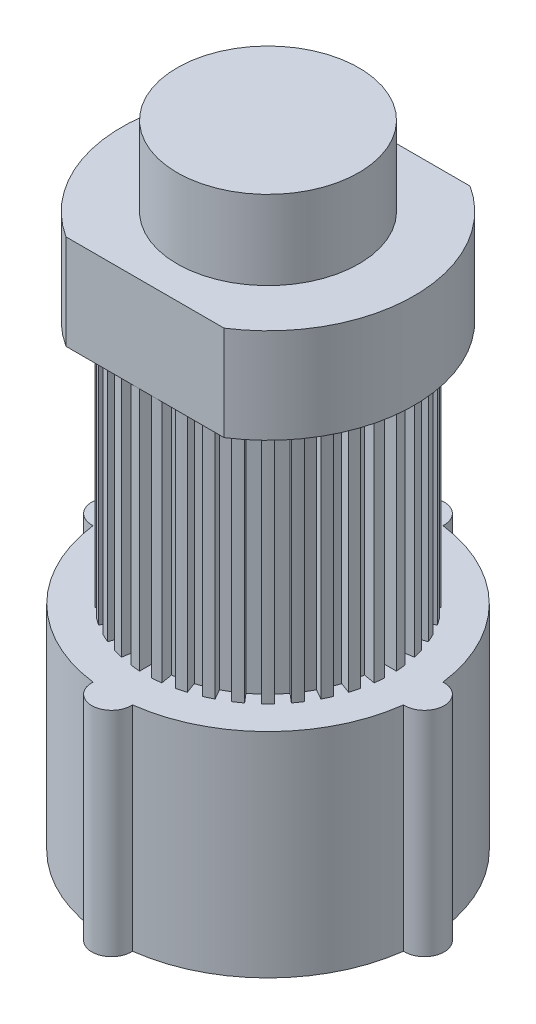
SolidWorks part; units mm, degrees
ref_plane "前视基准面" through (0, 0, 0) normal (0, 0, 1) x (1, 0, 0)
ref_plane "上视基准面" through (0, 0, 0) normal (0, 1, 0) x (1, 0, 0)
ref_plane "右视基准面" through (0, 0, 0) normal (1, 0, 0) x (0, 0, -1)
sketch "草图1" plane through (0, 0, 0) normal (0, 1, 0) x (1, 0, 0)
  circle A0 centre (0, 0) radius 8.2
  dimension "D1" = 16.4
extrude "凸台-拉伸1" add sketch "草图1" along normal blind 1
sketch "草图2" plane through (0, 1, 0) normal (0, 1, 0) x (1, 0, 0)
  line L0 (0, 12.8701) -> (0, -12.5799) construction
  line L1 (0, 0) -> (17.876, 0) construction
  circle A0 centre (0, 0) radius 19.799
  circle A2 centre (0, 19.799) radius 2.5
  circle A3 centre (19.799, 0) radius 2.5
  circle A4 centre (0, -19.799) radius 2.5
  circle A5 centre (-19.799, 0) radius 2.5
  point P19 (0, 0)
  circle M4 centre (0, 0) radius 8.2
  dimension "D2" = 5
  dimension "D3" = 4
  dimension "D4" = 28
extrude "凸台-拉伸2" add sketch "草图2" along normal blind 27 contours A5 A0 A4 A3 A2 M4 | M4 | A0 A3 | A0 A3 | A0 A2 | A0 A2 | A0 A5 | A0 A5 | A0 A4 | A0 A4
sketch "草图3" plane through (0, 28, 0) normal (0, 1, 0) x (1, 0, 0)
  circle A0 centre (0, 0) radius 15.5
  dimension "D1" = 31
extrude "凸台-拉伸4" add sketch "草图3" along normal offset from surface (43 mm away) 70 up to face at (0, 1, 8.2)
sketch "草图4" plane through (0, 71, 0) normal (0, 1, 0) x (1, 0, 0)
  circle A0 centre (0, 0) radius 11.5
  dimension "D1" = 23
extrude "凸台-拉伸5" add sketch "草图4" along normal blind 10
sketch "草图5" plane through (0, 71, 0) normal (0, 1, 0) x (1, 0, 0)
  line L0 (-18.5, 0) -> (18.5, 0) construction
  line L5 (-10, 15.5644) -> (10, 15.5644)
  line L6 (-10, -15.5644) -> (10, -15.5644)
  arc A8 (10, -15.5644) -> (10, 15.5644) centre (0, 0) ccw
  arc A9 (-10, -15.5644) -> (10, -15.5644) centre (0, 0) ccw construction
  arc A10 (10, 15.5644) -> (-10, 15.5644) centre (0, 0) ccw construction
  arc A11 (-10, 15.5644) -> (-10, -15.5644) centre (0, 0) ccw
  dimension "D2" = 20
  dimension "D1" = 37
extrude "凸台-拉伸6" add sketch "草图5" against normal blind 12
sketch "草图6" plane through (0, 28, 0) normal (0, 1, 0) x (1, 0, 0)
  line L0 (0, 0) -> (-18.4515, 0) construction
  line L2 (-17, -0.75) -> (-14, -0.75)
  line L3 (-17, -0.75) -> (-17, 0.75)
  line L4 (-17, 0.75) -> (-14, 0.75)
  line L5 (-14, -0.75) -> (-14, 0.75)
  line L6 (-17, -0.75) -> (-14, 0.75) construction
  line L7 (-17, 0.75) -> (-14, -0.75) construction
  circle A0 centre (0, 0) radius 15.5 construction
  circle A1 centre (0, 0) radius 15.5
  point P3 (-15.5, 0)
  circle M4 centre (0, 0) radius 15.5
  dimension "D1" = 1.5
  dimension "D2" = 3
extrude "切除-拉伸1" cut sketch "草图6" along normal up to surface (31 mm away) contours L4 L3 L2 M4 | L2 L5 L4 M4
pattern_circular "阵列(圆周)1" count 36 every 10 about axis through (0, 0, 0) along (0, 1, 0) of "切除-拉伸1"
sketch "草图7" plane through (0, 0, 0) normal (0, -1, 0) x (1, 0, 0)
  circle A1 centre (0, 0) radius 2.5
  dimension "D1" = 5
extrude "凸台-拉伸7" add sketch "草图7" along normal blind 10
ref_plane "基准面1" through (0, -9, 0) normal (0, -1, 0) x (-1, 0, 0)
sketch "草图9" plane through (0, -9, 0) normal (0, -1, 0) x (-1, 0, 0)
  line L1 (2.5, 0) -> (0, -2.5)
  line L2 (0, -2.5) -> (-2.5, 0)
  circle A1 centre (0, 0) radius 2.5
  arc A2 (-2.5, 0) -> (2.5, 0) centre (0, 0) ccw
  dimension "D1" = 0
extrude "切除-拉伸2" cut sketch "草图9" against normal blind 5 contours L2 A2 | L1 A2
sketch "草图10" plane through (0, 1, 0) normal (0, -1, 0) x (1, 0, 0)
  line L0 (-19.799, 0) -> (0, -19.799) construction
  line L1 (0, 0) -> (-9.8995, -9.8995) construction
  circle A0 centre (0, 0) radius 14.3677 construction
  arc A1 (-2.495, -19.6412) -> (2.495, -19.6412) centre (0, -19.799) ccw construction
  arc A2 (-19.6412, 2.495) -> (-19.6412, -2.495) centre (-19.799, 0) ccw construction
  arc A3 (-2.495, -19.6412) -> (2.495, -19.6412) centre (0, -19.799) ccw construction
  arc A4 (-19.6412, 2.495) -> (-19.6412, -2.495) centre (-19.799, 0) ccw construction
  circle A5 centre (-10.1595, -10.1595) radius 1.5
  circle A6 centre (-3.7186, 13.8781) radius 1.5
  circle A7 centre (13.8781, -3.7186) radius 1.5
  point P19 (0, 0)
  dimension "D1" = 3
  dimension "D2" = 3
extrude "切除-拉伸3" cut sketch "草图10" against normal blind 15
